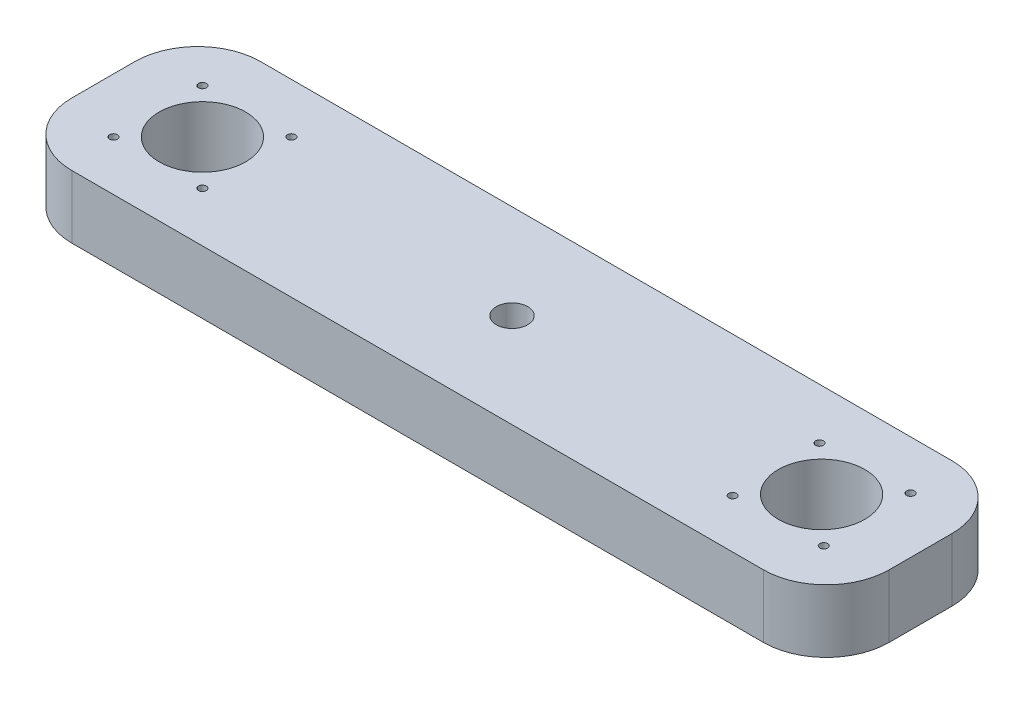
SolidWorks part; units mm, degrees
ref_plane "Front Plane" through (0, 0, 0) normal (0, 0, 1) x (1, 0, 0)
ref_plane "Top Plane" through (0, 0, 0) normal (0, 1, 0) x (1, 0, 0)
ref_plane "Right Plane" through (0, 0, 0) normal (1, 0, 0) x (0, 0, -1)
sketch "Sketch4" plane through (0, 0, 0) normal (0, 1, 0) x (1, 0, 0)
  line L1 (233.8279, -38.1) -> (-45.3721, -38.1)
  line L2 (259.2279, -12.7) -> (259.2279, 12.7)
  line L3 (233.8279, 38.1) -> (-45.3721, 38.1)
  line L4 (-70.7721, -12.7) -> (-70.7721, 12.7)
  line L5 (259.2279, -38.1) -> (-70.7721, 38.1) construction
  line L6 (259.2279, 38.1) -> (-70.7721, -38.1) construction
  arc A0 (259.2279, 12.7) -> (233.8279, 38.1) centre (233.8279, 12.7) ccw
  arc A1 (233.8279, -38.1) -> (259.2279, -12.7) centre (233.8279, -12.7) ccw
  arc A2 (-45.3721, -38.1) -> (-70.7721, -12.7) centre (-45.3721, -12.7) cw
  arc A3 (-45.3721, 38.1) -> (-70.7721, 12.7) centre (-45.3721, 12.7) ccw
  point P0 (0, 0)
  dimension "D3" = 25.4
  dimension "D1" = 76.2
  dimension "D2" = 330
extrude "Boss-Extrude1" add sketch "Sketch4" along normal blind 25.4
sketch "Sketch5" plane through (0, 25.4, 0) normal (0, 1, 0) x (1, 0, 0)
  line L2 (-70.7721, 12.7) -> (-70.7721, -12.7) construction
  line L3 (-45.3721, -38.1) -> (233.8279, -38.1) construction
  circle A0 centre (94.2279, 0) radius 6.35
  circle A1 centre (-30.7721, 0) radius 17.4625
  circle A2 centre (219.2279, 0) radius 17.4625
  dimension "D1" = 12.7
  dimension "D6" = 34.925
  dimension "D2" = 165
  dimension "D3" = 38.1
  dimension "D4" = 125
  dimension "D5" = 125
extrude "Cut-Extrude1" cut sketch "Sketch5" against normal up to next
sketch "Sketch6" plane through (0, 0, 0) normal (0, -1, 0) x (1, 0, 0)
  line L0 (-30.7721, 0) -> (-48.7326, 17.9605)
  line L1 (-30.7721, 0) -> (-12.8115, 17.9605)
  line L2 (-30.7721, 0) -> (-12.8115, -17.9605)
  line L3 (-30.7721, 0) -> (-48.7326, -17.9605)
  line L5 (201.7096, 18.392) -> (219.2279, 0)
  line L6 (219.2279, 0) -> (237.62, 17.5184)
  line L7 (236.7463, -18.392) -> (219.2279, 0)
  line L8 (219.2279, 0) -> (200.8359, -17.5184)
  circle A0 centre (201.7096, 18.392) radius 1.5875
  circle A1 centre (237.62, 17.5184) radius 1.5875
  circle A2 centre (236.7463, -18.392) radius 1.5875
  circle A3 centre (200.8359, -17.5184) radius 1.5875
  circle A5 centre (-48.7326, 17.9605) radius 1.5875
  circle A6 centre (-12.8115, 17.9605) radius 1.5875
  circle A7 centre (-12.8115, -17.9605) radius 1.5875
  circle A8 centre (-48.7326, -17.9605) radius 1.5875
  point P9 (219.2279, 0)
  point P12 (-30.7721, 0)
  dimension "D2" = 3.175
  dimension "D4" = 3.175
  dimension "D1" = 25.4
  dimension "D3" = 25.4
extrude "Cut-Extrude2" cut sketch "Sketch6" against normal up to next contours A8 | A7 | A6 | A5 | A3 | A2 | A1 | A0
